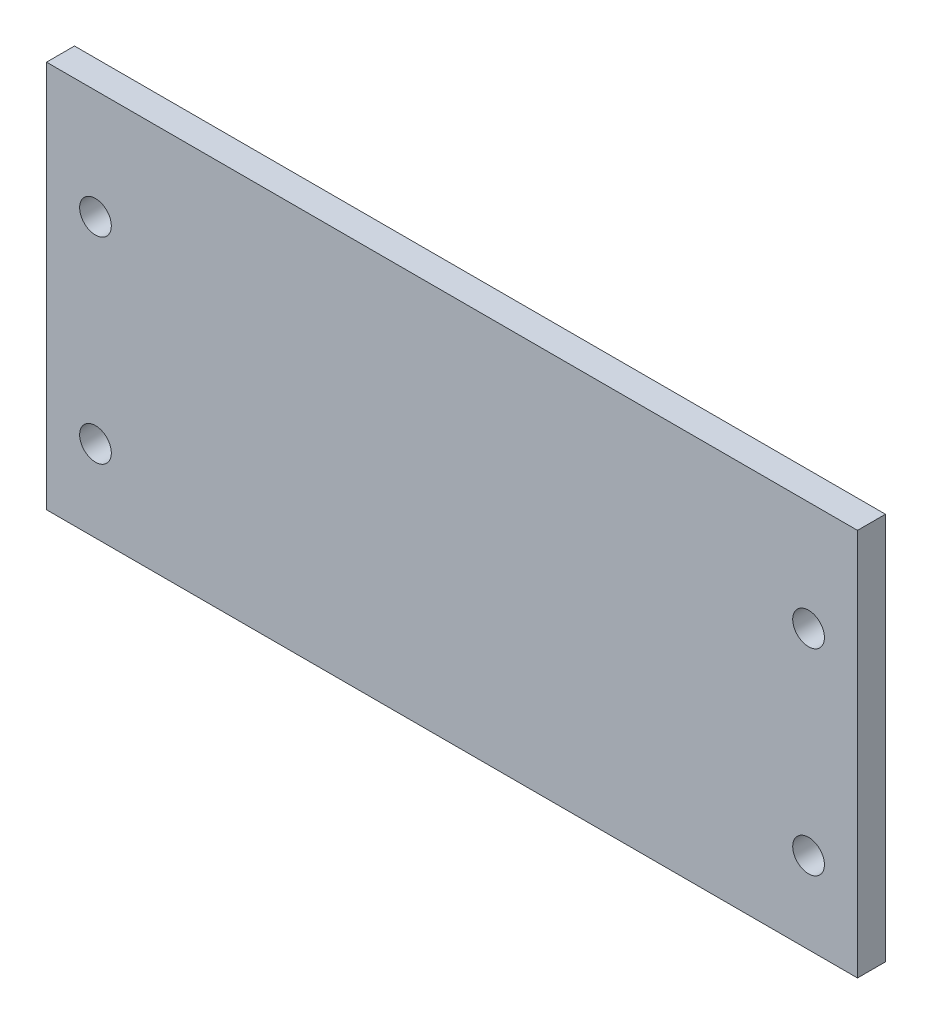
SolidWorks part; units mm, degrees
ref_plane "Front Plane" through (0, 0, 0) normal (0, 0, 1) x (1, 0, 0)
ref_plane "Top Plane" through (0, 0, 0) normal (0, 1, 0) x (1, 0, 0)
ref_plane "Right Plane" through (0, 0, 0) normal (1, 0, 0) x (0, 0, -1)
sketch "Sketch1" plane through (0, 0, 0) normal (0, 0, 1) x (1, 0, 0)
  line L1 (0, 0) -> (87, 0)
  line L2 (0, 0) -> (0, 41.59)
  line L3 (0, 41.59) -> (87, 41.59)
  line L4 (87, 0) -> (87, 41.59)
  circle A0 centre (5.25, 29.85) radius 1.7
  circle A2 centre (5.25, 8.75) radius 1.7
  circle A3 centre (81.75, 8.75) radius 1.7
  circle A4 centre (81.75, 29.85) radius 1.7
  dimension "D3" = 3.4
  dimension "D4" = 3.4
  dimension "D5" = 8.75
  dimension "D6" = 3.4
  dimension "D7" = 3.4
  dimension "D8" = 21.1
  dimension "D9" = 21.1
  dimension "D10" = 5.25
  dimension "D11" = 8.75
  dimension "D12" = 5.25
  dimension "D13" = 11.74
  dimension "D14" = 5.25
  dimension "D15" = 5.25
  dimension "D1" = 41.59
  dimension "D2" = 87
extrude "Boss-Extrude1" add sketch "Sketch1" along normal blind 3 contours L1 L4 L3 L2 A4 A3 A2 A0
